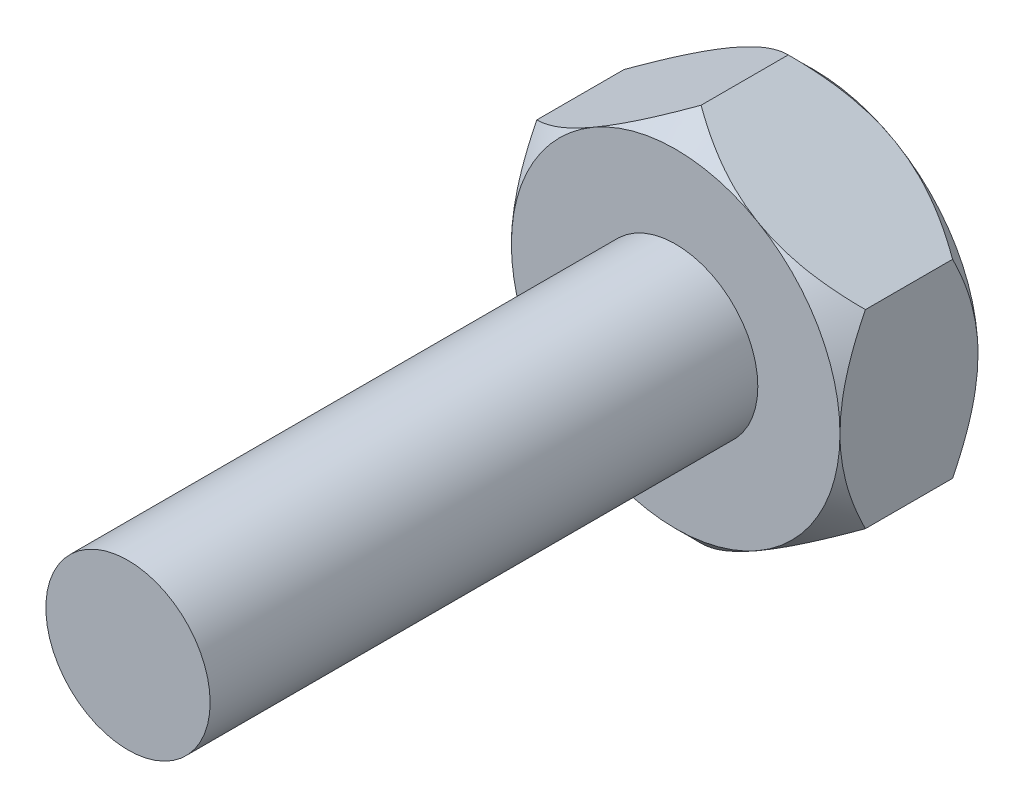
SolidWorks part; units mm, degrees
ref_plane "Alzado" through (0, 0, 0) normal (0, 0, 1) x (1, 0, 0)
ref_plane "Planta" through (0, 0, 0) normal (0, 1, 0) x (1, 0, 0)
ref_plane "Vista lateral" through (0, 0, 0) normal (1, 0, 0) x (0, 0, -1)
sketch "Sketch1" plane through (0, 0, 0) normal (0, 0, 1) x (1, 0, 0)
  circle A0 centre (0, 0) radius 1.5
extrude "Boss-Extrude1" add sketch "Sketch1" along normal blind 10
sketch "Sketch6" plane through (0, 0, 0) normal (0, 0, -1) x (-1, 0, 0)
  line L2 (0, -3.4641) -> (3, -1.7321)
  line L3 (3, -1.7321) -> (3, 1.7321)
  line L4 (3, 1.7321) -> (0, 3.4641)
  line L5 (0, 3.4641) -> (-3, 1.7321)
  line L6 (-3, 1.7321) -> (-3, -1.7321)
  line L7 (-3, -1.7321) -> (0, -3.4641)
  circle A0 centre (0, 0) radius 3 construction
  dimension "D1" = 6
extrude "Boss-Extrude3" add sketch "Sketch6" along normal blind 2.52
sketch "Sketch7" plane through (0, 0, -2.52) normal (0, 0, -1) x (-1, 0, 0)
  circle A0 centre (0, 0) radius 3
extrude "Cut-Extrude3" cut sketch "Sketch7" against normal through all draft 45 flip side to cut
sketch "Sketch8" plane through (0, 0, 0) normal (0, 0, 1) x (1, 0, 0)
  circle A0 centre (0, 0) radius 3
extrude "Cut-Extrude5" cut sketch "Sketch8" against normal through all draft 45 flip side to cut
sketch "Sketch9" plane through (0, 0, -2.52) normal (0, 0, -1) x (-1, 0, 0)
